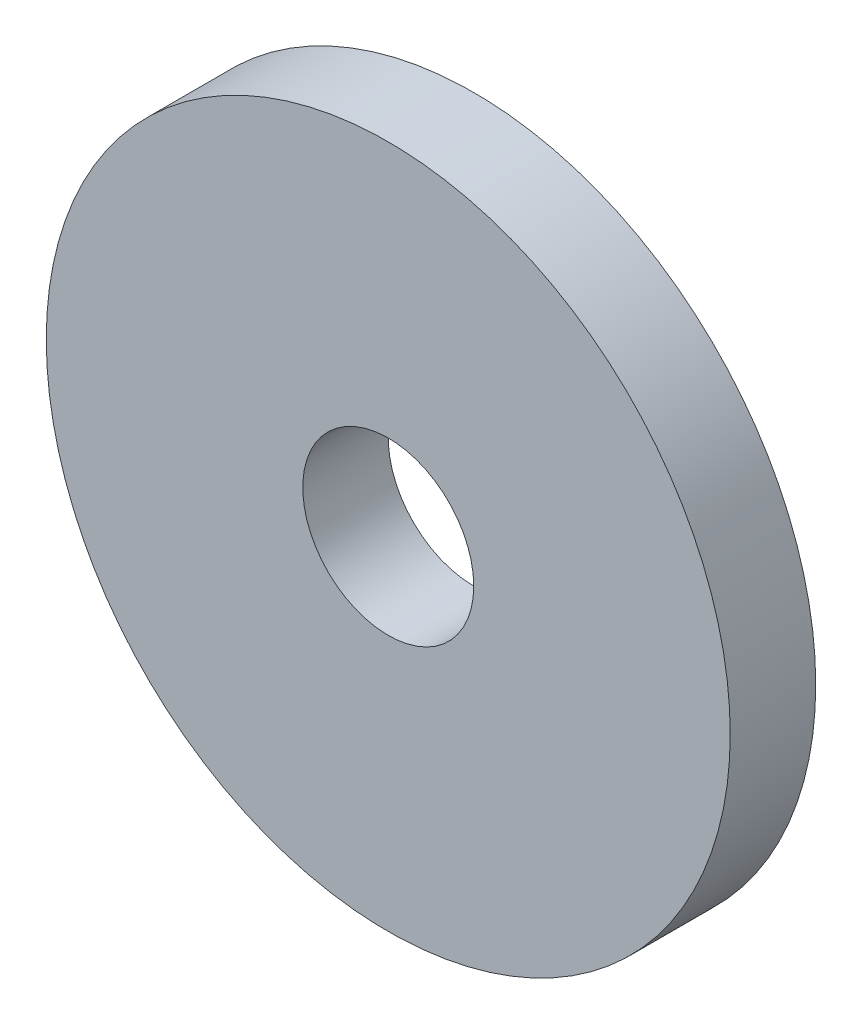
SolidWorks part; units mm, degrees
material "ABS"
ref_plane "Front Plane" through (0, 0, 0) normal (0, 0, 1) x (1, 0, 0)
ref_plane "Top Plane" through (0, 0, 0) normal (0, 1, 0) x (1, 0, 0)
ref_plane "Right Plane" through (0, 0, 0) normal (1, 0, 0) x (0, 0, -1)
sketch "Sketch1" plane through (0, 0, 0) normal (0, 0, 1) x (1, 0, 0)
  circle A0 centre (0, 0) radius 4
  circle A1 centre (0, 0) radius 1
  dimension "D1" = 8
  dimension "D2" = 2
extrude "Boss-Extrude1" add sketch "Sketch1" along normal blind 1
equation "\"Flange Diameter\"= 8"
equation "\"Bolt Diameter\"= 2"
equation "\"Flange Thickness\"= 1"
equation "\"D1@Sketch1\"=\"Flange Diameter\""
equation "\"D2@Sketch1\"=\"Bolt Diameter\""
equation "\"D1@Boss-Extrude1\"=\"Flange Thickness\""
